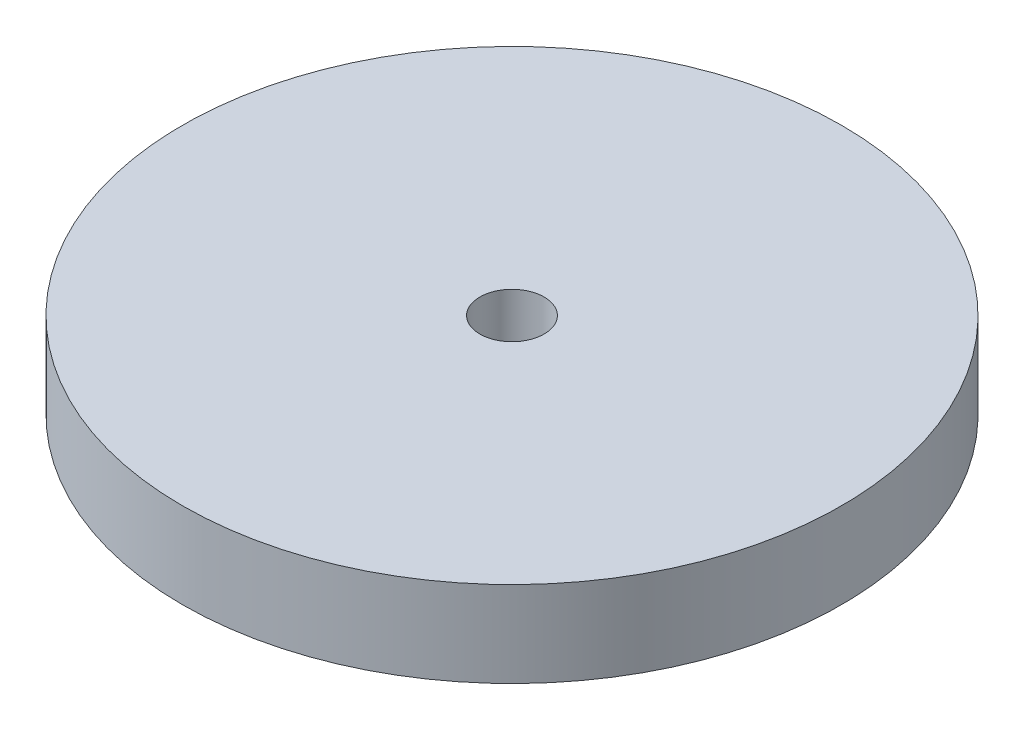
SolidWorks part; units mm, degrees
material "PF"
ref_plane "Front Plane" through (0, 0, 0) normal (0, 0, 1) x (1, 0, 0)
ref_plane "Top Plane" through (0, 0, 0) normal (0, 1, 0) x (1, 0, 0)
ref_plane "Right Plane" through (0, 0, 0) normal (1, 0, 0) x (0, 0, -1)
sketch "Sketch1" plane through (0, 0, 0) normal (0, 1, 0) x (1, 0, 0)
  circle A0 centre (0, 0) radius 76.895
  dimension "D1" = 153.79
extrude "Boss-Extrude1" add sketch "Sketch1" along normal blind 20
sketch "Sketch2" plane through (0, 20, 0) normal (0, 1, 0) x (1, 0, 0)
  circle A0 centre (0, 0) radius 7.5
  dimension "D1" = 15
extrude "Cut-Extrude1" cut sketch "Sketch2" against normal up to next
